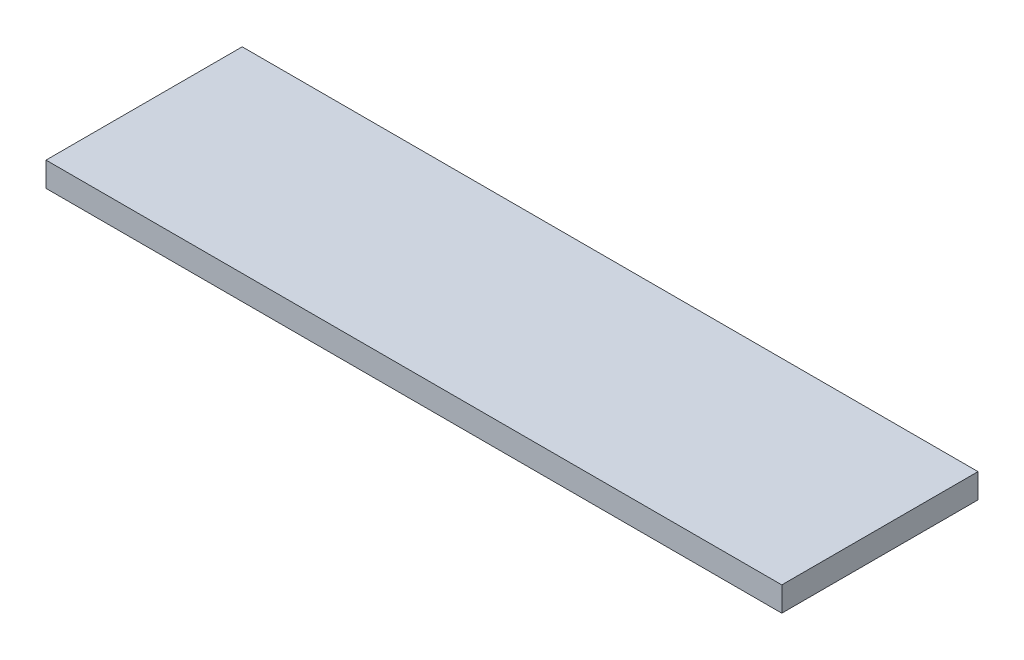
SolidWorks part; units mm, degrees
ref_plane "Front Plane" through (0, 0, 0) normal (0, 0, 1) x (1, 0, 0)
ref_plane "Top Plane" through (0, 0, 0) normal (0, 1, 0) x (1, 0, 0)
ref_plane "Right Plane" through (0, 0, 0) normal (1, 0, 0) x (0, 0, -1)
sketch "Sketch1" plane through (0, 0, 0) normal (0, 1, 0) x (1, 0, 0)
  line L1 (-15, 4) -> (15, 4)
  line L2 (-15, 4) -> (-15, -4)
  line L3 (-15, -4) -> (15, -4)
  line L4 (15, 4) -> (15, -4)
  line L5 (-15, 4) -> (15, -4) construction
  line L6 (-15, -4) -> (15, 4) construction
  point P0 (0, 0)
  dimension "D1" = 30
  dimension "D2" = 8
extrude "Boss-Extrude1" add sketch "Sketch1" along normal blind 1
